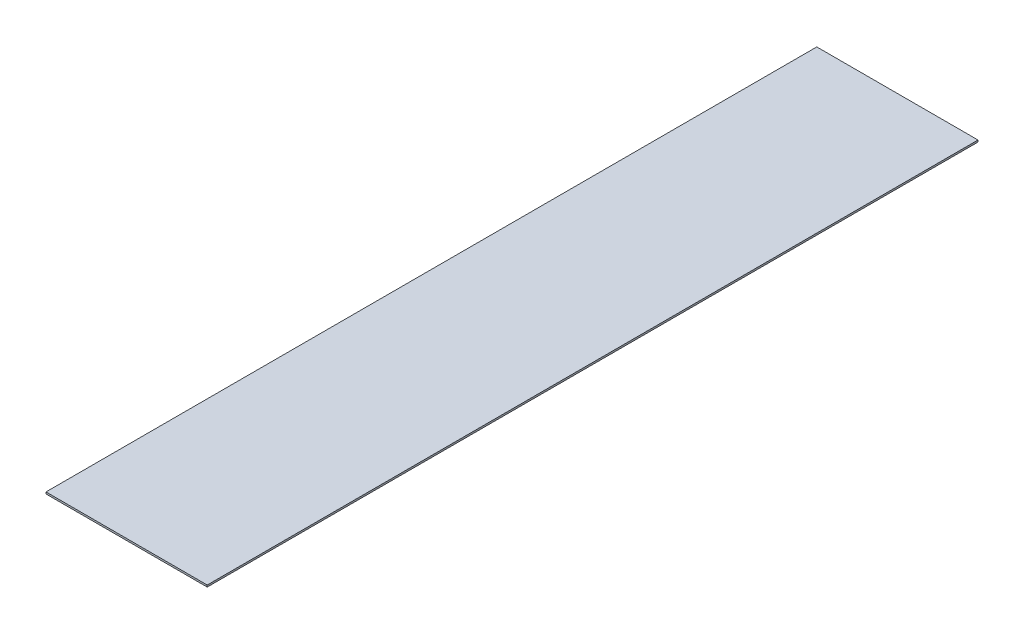
SolidWorks part; units mm, degrees
ref_plane "Front Plane" through (0, 0, 0) normal (0, 0, 1) x (1, 0, 0)
ref_plane "Top Plane" through (0, 0, 0) normal (0, 1, 0) x (1, 0, 0)
ref_plane "Right Plane" through (0, 0, 0) normal (1, 0, 0) x (0, 0, -1)
sketch "Sketch1" plane through (0, 0, 0) normal (0, 1, 0) x (1, 0, 0)
  line L1 (-44.45, 212.5) -> (44.45, 212.5)
  line L2 (-44.45, 212.5) -> (-44.45, -212.5)
  line L3 (-44.45, -212.5) -> (44.45, -212.5)
  line L4 (44.45, 212.5) -> (44.45, -212.5)
  line L5 (-44.45, 212.5) -> (44.45, -212.5) construction
  line L6 (-44.45, -212.5) -> (44.45, 212.5) construction
  point P0 (0, 0)
  dimension "D1" = 425
  dimension "D2" = 88.9
extrude "Boss-Extrude1" add sketch "Sketch1" along normal blind 1
